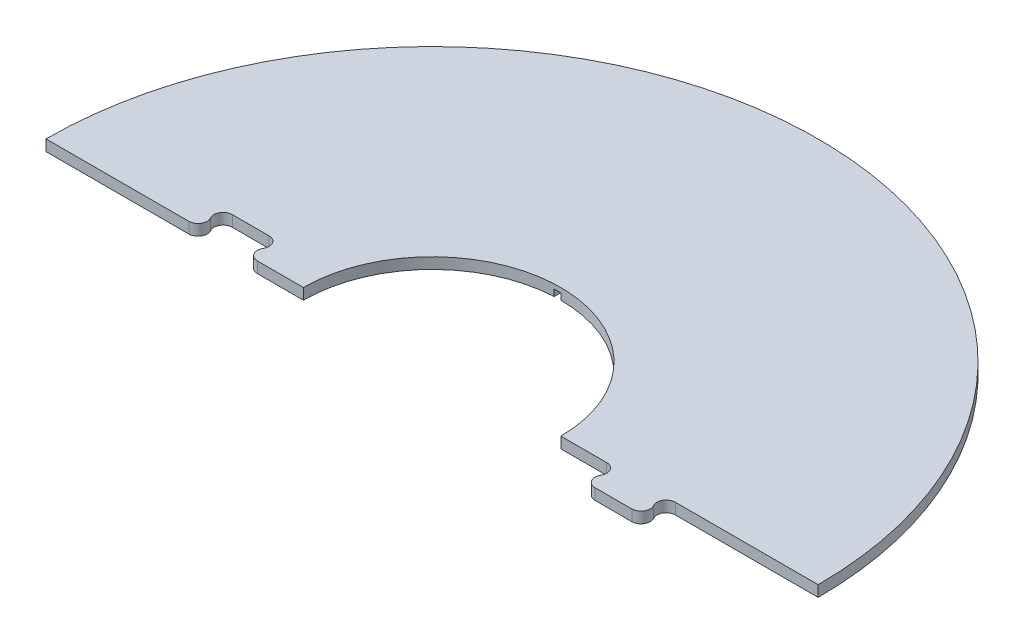
SolidWorks part; units mm, degrees
ref_plane "Front Plane" through (0, 0, 0) normal (0, 0, 1) x (1, 0, 0)
ref_plane "Top Plane" through (0, 0, 0) normal (0, 1, 0) x (1, 0, 0)
ref_plane "Right Plane" through (0, 0, 0) normal (1, 0, 0) x (0, 0, -1)
sketch "Sketch1" plane through (0, 0, 0) normal (0, 1, 0) x (1, 0, 0)
  line L0 (-420, 0) -> (-264.641, 0)
  line L1 (190, 0) -> (140, 0)
  line L2 (-190, 0) -> (-140, 0)
  line L3 (207.3205, -30) -> (247.3205, -30)
  line L4 (-207.3205, 30) -> (-247.3205, 30)
  line L5 (420, 0) -> (264.641, 0)
  arc A0 (140, 0) -> (-140, 0) centre (0, 0) ccw
  arc A1 (420, 0) -> (-420, 0) centre (0, 0) ccw
  arc A2 (-190, 0) -> (-198.6603, 15) centre (-190, 10) cw
  arc A3 (-207.3205, 30) -> (-198.6603, 15) centre (-207.3205, 20) cw
  arc A4 (-255.9808, 15) -> (-264.641, 0) centre (-264.641, 10) cw
  arc A6 (190, 0) -> (198.6603, -15) centre (190, -10) cw
  arc A7 (207.3205, -30) -> (198.6603, -15) centre (207.3205, -20) cw
  arc A8 (-247.3205, 30) -> (-255.9808, 15) centre (-247.3205, 20) ccw
  arc A9 (247.3205, -30) -> (255.9808, -15) centre (247.3205, -20) ccw
  arc A10 (255.9808, -15) -> (264.641, 0) centre (264.641, -10) cw
  point P25 (0, 0)
  point P35 (0, 0)
  dimension "D1" = 420
  dimension "D2" = 140
  dimension "D3" = 10
  dimension "D7" = 40
  dimension "D4" = 50
  dimension "D5" = 30
  dimension "D6" = 2
extrude "Boss-Extrude1" add sketch "Sketch1" along normal blind 12
sketch "Sketch2" plane through (0, 0, 0) normal (0, -1, 0) x (1, 0, 0)
  line L0 (-7, -139.8249) -> (-7, -419.9417)
  line L1 (0, -140) -> (0, -420)
  arc A0 (-140, 0) -> (140, 0) centre (0, 0) ccw construction
  arc A1 (-420, 0) -> (420, 0) centre (0, 0) ccw construction
  arc M3 (-420, 0) -> (420, 0) centre (0, 0) ccw
  arc M11 (140, 0) -> (-140, 0) centre (0, 0) cw
  dimension "D1" = 7
extrude "Cut-Extrude1" cut sketch "Sketch2" against normal blind 7 contours L1 L0 M11 M3
